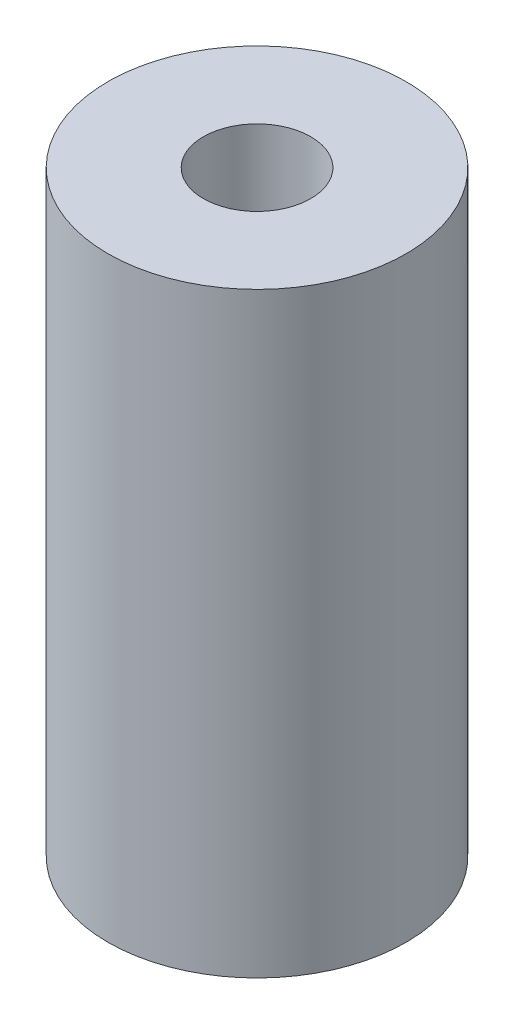
SolidWorks part; units mm, degrees
ref_plane "Front Plane" through (0, 0, 0) normal (0, 0, 1) x (1, 0, 0)
ref_plane "Top Plane" through (0, 0, 0) normal (0, 1, 0) x (1, 0, 0)
ref_plane "Right Plane" through (0, 0, 0) normal (1, 0, 0) x (0, 0, -1)
sketch "Sketch1" plane through (0, 0, 0) normal (0, 1, 0) x (1, 0, 0)
  circle A0 centre (0, 0) radius 3.175
extrude "Boss-Extrude3" add sketch "Sketch1" along normal blind 12.7 contours A0
sketch "Sketch2" plane through (0, 0, 0) normal (0, -1, 0) x (-1, 0, 0)
  circle A0 centre (0, 0) radius 1.143
  circle A1 centre (0, 0) radius 3.175 construction
  dimension "D1" = 2.032
extrude "Cut-Extrude1" cut sketch "Sketch2" against normal blind 12.7
